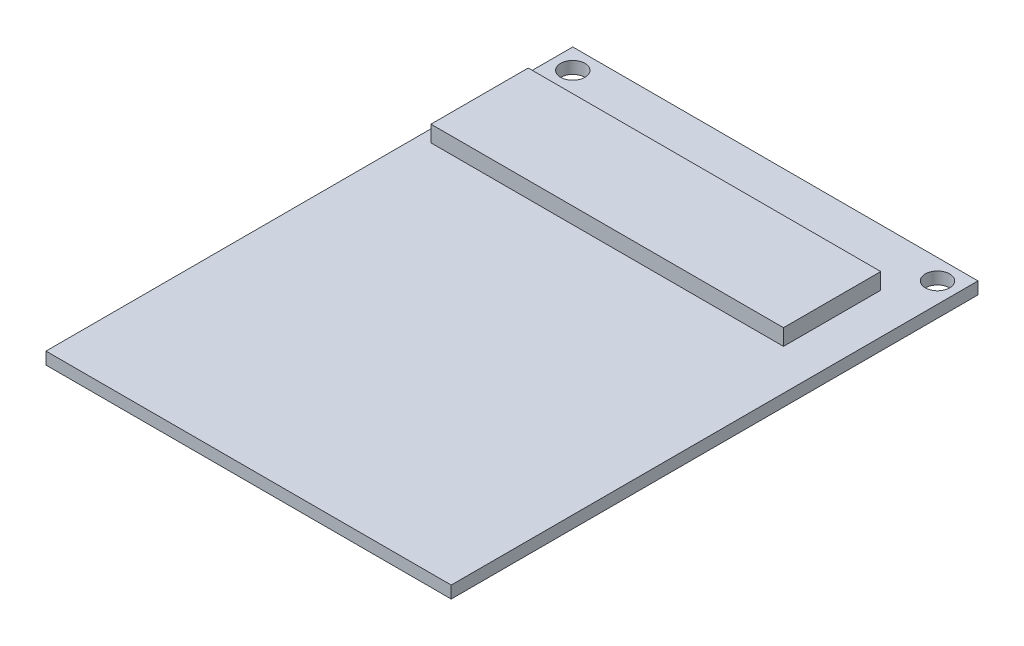
SolidWorks part; units mm, degrees
ref_plane "Front Plane" through (0, 0, 0) normal (0, 0, 1) x (1, 0, 0)
ref_plane "Top Plane" through (0, 0, 0) normal (0, 1, 0) x (1, 0, 0)
ref_plane "Right Plane" through (0, 0, 0) normal (1, 0, 0) x (0, 0, -1)
sketch "Sketch1" plane through (0, 0, 0) normal (0, 1, 0) x (1, 0, 0)
  line L0 (0, 44) -> (50, 44)
  line L1 (0, 0) -> (50, 0)
  line L2 (0, 0) -> (0, 65)
  line L3 (0, 65) -> (50, 65)
  line L4 (50, 0) -> (50, 65)
  dimension "D1" = 50
  dimension "D2" = 65
  dimension "D3" = 44
extrude "Boss-Extrude1" add sketch "Sketch1" along normal blind 1.5 contours L1 L4 L0 L2 | L0 L4 L3 L2
sketch "Sketch2" plane through (0, 1.5, 0) normal (0, 1, 0) x (1, 0, 0)
  line L0 (0, 0) -> (0, 65) construction
  line L1 (0, 46) -> (50, 46)
  line L2 (50, 0) -> (50, 65) construction
  line L3 (0, 65) -> (50, 65) construction
  line L5 (0, 46) -> (50, 46)
  line L6 (0, 46) -> (0, 65)
  line L7 (0, 65) -> (50, 65)
  line L8 (0, 0) -> (50, 0)
  line L9 (50, 0) -> (50, 65)
  line L10 (50, 65) -> (0, 65)
  line L11 (0, 65) -> (0, 0)
  line L12 (0, 0) -> (50, 0)
  line L13 (50, 0) -> (50, 46)
  line L15 (0, 46) -> (0, 0)
  line L16 (50, 46) -> (50, 65)
  line L17 (0, 46) -> (50, 46)
  line L18 (0, 46) -> (0, 65)
  line L19 (0, 65) -> (50, 65)
  line L20 (50, 46) -> (50, 65)
  line L21 (0, 58) -> (50, 58) construction
  line L22 (1.5, 65) -> (1.5, 46) construction
  line L23 (45, 65) -> (45, 46) construction
  line L24 (45, 46) -> (1.5, 46)
  line L25 (45, 46) -> (45, 58)
  line L26 (45, 58) -> (1.5, 58)
  line L27 (1.5, 46) -> (1.5, 58)
  dimension "D1" = 19
  dimension "D3" = 1.5
  dimension "D4" = 5
  dimension "D5" = 7
  dimension "D2" = 0
extrude "Boss-Extrude3" add sketch "Sketch2" along normal blind 2 contours L27 L17 L25 L26
sketch "Sketch4" plane through (0, 1.5, 0) normal (0, 1, 0) x (1, 0, 0)
  line L1 (0, 0) -> (0, 65) construction
  line L2 (0, 65) -> (50, 65) construction
  line L3 (50, 0) -> (50, 65) construction
  circle A0 centre (2.5, 62.5) radius 1.5
  circle A1 centre (47.5, 62.5) radius 1.5
  dimension "D1" = 2.5
  dimension "D3" = 2.5
  dimension "D2" = 2.5
  dimension "D4" = 2.5
extrude "Cut-Extrude1" cut sketch "Sketch4" against normal up to surface (1.5 mm away) up to face at (25, 0, -32.5)
sketch "Sketch5" plane through (0, 1.5, 0) normal (0, 1, 0) x (1, 0, 0)
  line L0 (0, 0) -> (0, 65) construction
  line L1 (50, 0) -> (0, 0)
  line L2 (50, 0) -> (50, 45)
  line L3 (50, 45) -> (0, 45)
  line L4 (0, 0) -> (0, 45)
  line L5 (0, 45) -> (50, 0)
  text T0 "<b>KEYBOARD AREA</b>" font "Century Gothic" height 3.5
